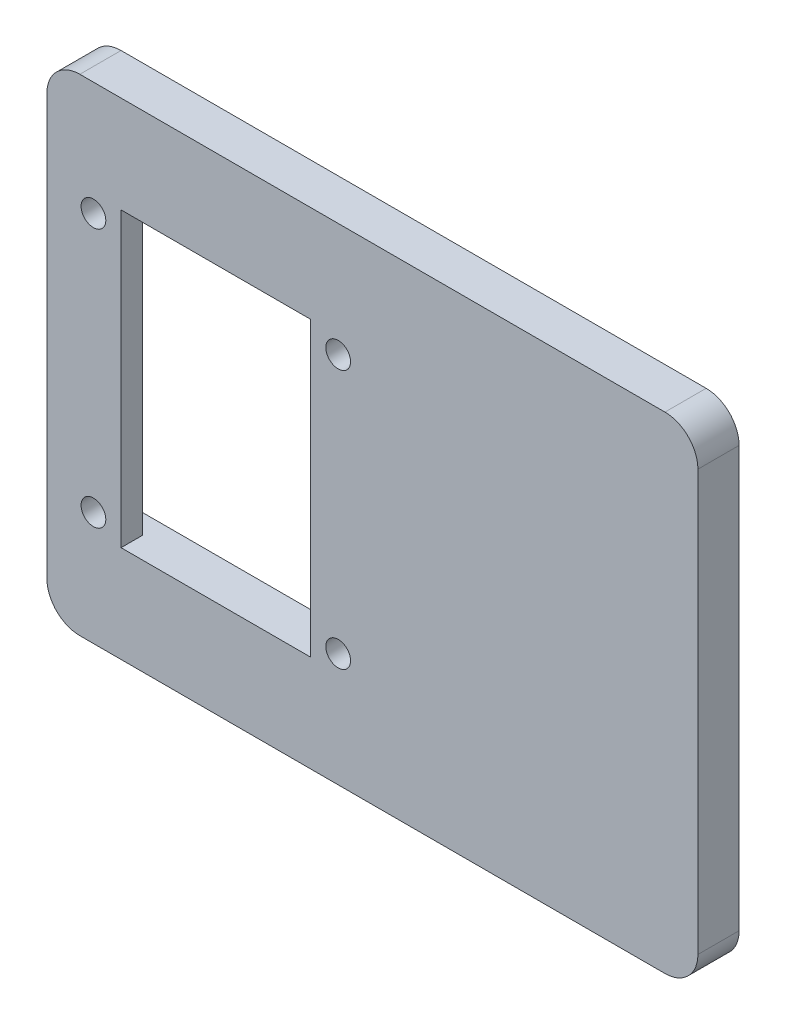
SolidWorks part; units mm, degrees
ref_plane "Front Plane" through (0, 0, 0) normal (0, 0, 1) x (1, 0, 0)
ref_plane "Top Plane" through (0, 0, 0) normal (0, 1, 0) x (1, 0, 0)
ref_plane "Right Plane" through (0, 0, 0) normal (1, 0, 0) x (0, 0, -1)
sketch "Sketch1" plane through (0, 0, 0) normal (0, 0, 1) x (1, 0, 0)
  line L1 (-39.5, -29.5) -> (39.5, -29.5)
  line L2 (-39.5, -29.5) -> (-39.5, 29.5)
  line L3 (-39.5, 29.5) -> (39.5, 29.5)
  line L4 (39.5, -29.5) -> (39.5, 29.5)
  line L5 (-39.5, -29.5) -> (39.5, 29.5) construction
  line L6 (-39.5, 29.5) -> (39.5, -29.5) construction
  point P0 (0, 0)
  dimension "D1" = 79
  dimension "D2" = 59
extrude "Boss-Extrude1" add sketch "Sketch1" along normal blind 5
sketch "Sketch2" plane through (0, 0, 5) normal (0, 0, 1) x (1, 0, 0)
  line L0 (0, 28) -> (0, -27.2265)
  line L1 (-38, -28) -> (38, -28)
  line L2 (-38, -28) -> (-38, 28)
  line L3 (-38, 28) -> (38, 28)
  line L4 (38, -28) -> (38, 28)
  line L5 (-38, -28) -> (38, 28) construction
  line L6 (-38, 28) -> (38, -28) construction
  line L7 (0, 0) -> (-38, 0)
  line L9 (-35.85, -17.75) -> (-2.15, -17.75)
  line L10 (-35.85, -17.75) -> (-35.85, 17.75)
  line L11 (-35.85, 17.75) -> (-2.15, 17.75)
  line L12 (-2.15, -17.75) -> (-2.15, 17.75)
  line L13 (-35.85, -17.75) -> (-2.15, 17.75) construction
  line L14 (-35.85, 17.75) -> (-2.15, -17.75) construction
  line L19 (-31.2628, -12.9178) -> (-6.7372, 12.9178) construction
  line L20 (-31.2628, 12.9178) -> (-6.7372, -12.9178) construction
  line L21 (-33.85, -15.71) -> (-4.15, -15.71) construction
  line L22 (-33.85, -15.71) -> (-33.85, 15.71) construction
  line L23 (-33.85, 15.71) -> (-4.15, 15.71) construction
  line L24 (-4.15, -15.71) -> (-4.15, 15.71) construction
  line L25 (-33.85, -15.71) -> (-4.15, 15.71) construction
  line L26 (-33.85, 15.71) -> (-4.15, -15.71) construction
  line L27 (-30.5, -17.75) -> (-7.5, -17.75)
  line L28 (-30.5, -17.75) -> (-30.5, 17.75)
  line L29 (-30.5, 17.75) -> (-7.5, 17.75)
  line L30 (-7.5, -17.75) -> (-7.5, 17.75)
  line L31 (-30.5, -17.75) -> (-7.5, 17.75) construction
  line L32 (-30.5, 17.75) -> (-7.5, -17.75) construction
  circle A0 centre (-33.85, 15.71) radius 1.5
  circle A1 centre (-33.85, -15.71) radius 1.5
  circle A2 centre (-4.15, 15.71) radius 1.5
  circle A3 centre (-4.15, -15.71) radius 1.5
  point P0 (0, 0)
  point P10 (-19, 0)
  point P15 (-19, 0)
  point P20 (-19, 0)
  point P27 (-19, 0)
  dimension "D7" = 3
  dimension "D1" = 76
  dimension "D2" = 56
  dimension "D3" = 33.7
  dimension "D4" = 35.5
  dimension "D5" = 29.7
  dimension "D6" = 31.42
  dimension "D8" = 23
  dimension "D9" = 35.5
extrude "Cut-Extrude1" cut sketch "Sketch2" against normal blind 2.6 contours A2 | A3 | A1 | A0 | L9 L30 L7 L28 | L7 L30 L11 L28
sketch "Sketch3" plane through (0, 0, 0) normal (0, 0, -1) x (-1, 0, 0)
  line L0 (0, -28) -> (0, 28)
  line L1 (38, 28) -> (-38, 28)
  line L2 (38, 28) -> (38, -28)
  line L3 (38, -28) -> (-38, -28)
  line L4 (-38, 28) -> (-38, -28)
  line L5 (38, 28) -> (-38, -28) construction
  line L6 (38, -28) -> (-38, 28) construction
  line L9 (35.85, 17.75) -> (2.15, 17.75)
  line L10 (35.85, 17.75) -> (35.85, -17.75)
  line L11 (35.85, -17.75) -> (2.15, -17.75)
  line L12 (2.15, 17.75) -> (2.15, -17.75)
  line L13 (35.85, 17.75) -> (2.15, -17.75) construction
  line L14 (35.85, -17.75) -> (2.15, 17.75) construction
  point P0 (0, 0)
  point P10 (19, 0)
  dimension "D1" = 76
  dimension "D2" = 56
  dimension "D3" = 33.7
  dimension "D4" = 35.5
extrude "Cut-Extrude2" cut sketch "Sketch3" against normal blind 2.4 contours L9 L12 L11 L10
fillet "Fillet1" radius 4 4 edges at (-39.5, 29.5, 2.5) (-39.5, -29.5, 2.5) (39.5, -29.5, 2.5) (39.5, 29.5, 2.5)
